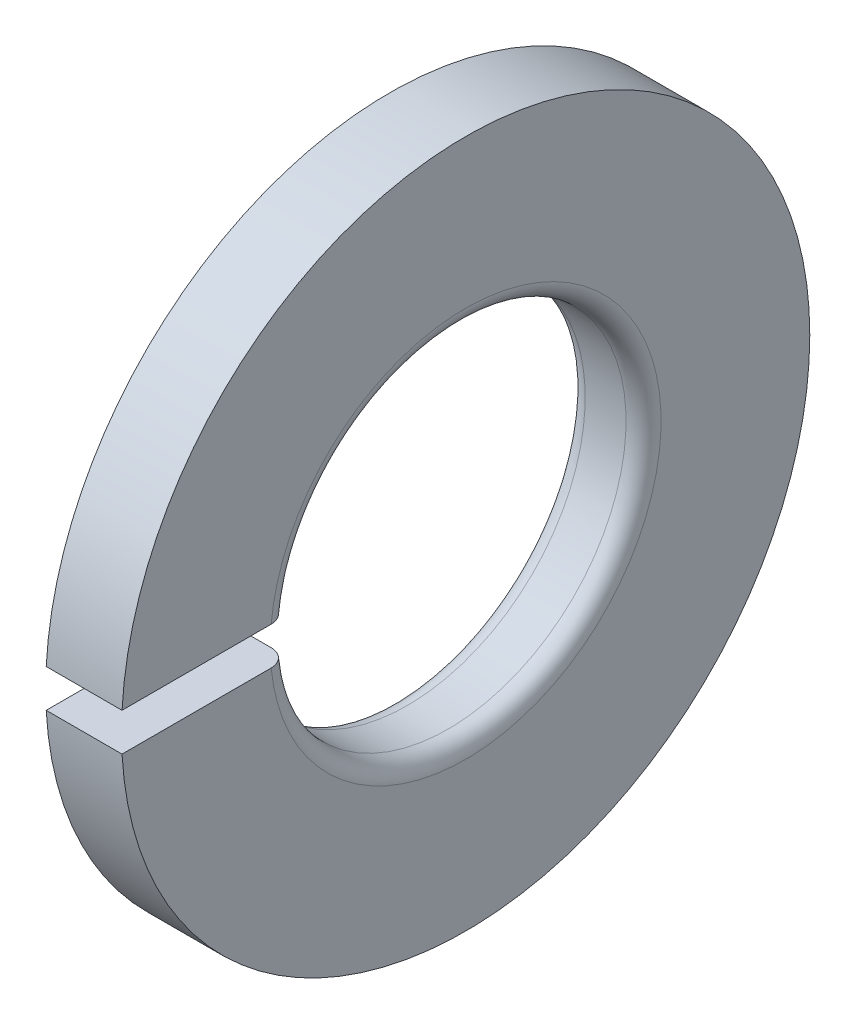
SolidWorks part; units mm, degrees
ref_plane "Plane1" through (0, 0, 0) normal (0, 0, 1) x (1, 0, 0)
ref_plane "Plane2" through (0, 0, 0) normal (0, 1, 0) x (1, 0, 0)
ref_plane "Plane3" through (0, 0, 0) normal (1, 0, 0) x (0, 0, -1)
sketch "Sketch1" plane through (0, 0, 0) normal (0, 0, 1) x (1, 0, 0)
  line L0 (-34.925, 0) -> (9.525, 0) construction
  line L1 (0, 3.35) -> (0, 5.9)
  line L2 (0, 5.9) -> (-1.3, 5.9)
  line L3 (-1.3, 5.9) -> (-1.3, 3.35)
  line L4 (-1, 3.05) -> (-0.3, 3.05)
  arc A0 (-1, 3.05) -> (-1.3, 3.35) centre (-1, 3.35) cw
  arc A1 (0, 3.35) -> (-0.3, 3.05) centre (-0.3, 3.35) cw
  point P8 (-1.3, 3.05)
  dimension "D1" = 0.2
revolve "Base-Revolve" add sketch "Sketch1" angle 360 about L0
sketch "Sketch2" plane through (0, 0, 0) normal (-1, 0, 0) x (0, -1, 0)
  line L0 (-0.325, 0) -> (0.325, 0)
  line L1 (0, 0) -> (0, 12.7) construction
  line L2 (0.325, 0) -> (0.325, 6.018)
  line L3 (0.325, 6.018) -> (-0.325, 6.018)
  line L4 (-0.325, 6.018) -> (-0.325, 0)
  dimension "D1" = 0.5
  dimension "D2" = 4.692
extrude "Gap" cut sketch "Sketch2" along normal through all
equation "\"D1@Sketch1\" = \"Fillet_rad@Sketch1\""
equation "\"D1@Sketch2\" = \"Thickness@Sketch1\" * 0.5"
equation "\"D2@Sketch2\" = \"Outside_dia@Sketch1\" * 0.51"
